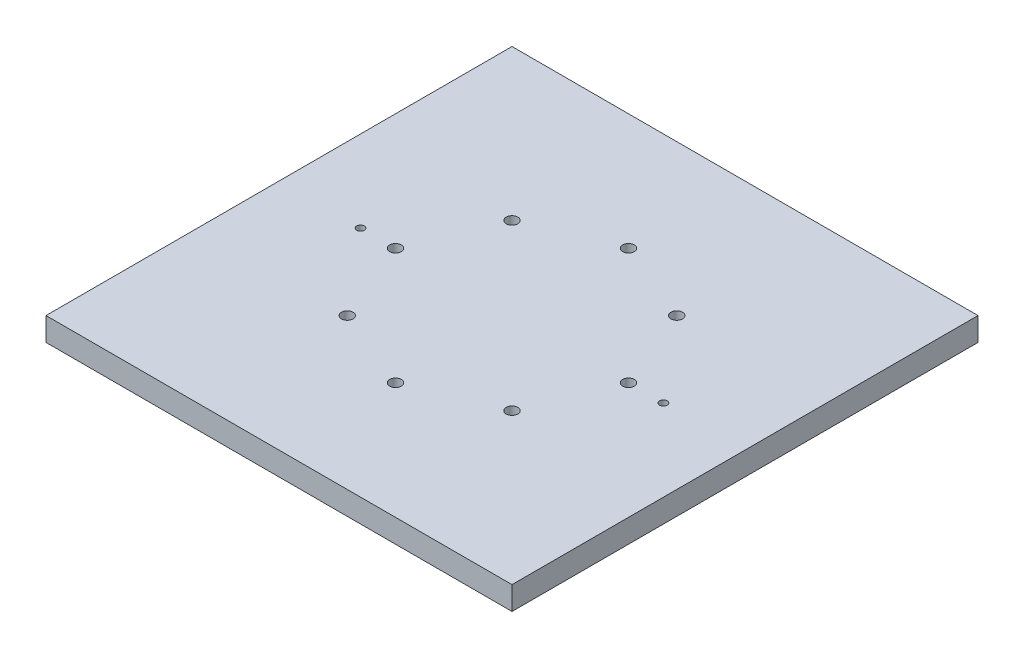
SolidWorks part; units mm, degrees
ref_plane "Front Plane" through (0, 0, 0) normal (0, 0, 1) x (1, 0, 0)
ref_plane "Top Plane" through (0, 0, 0) normal (0, 1, 0) x (1, 0, 0)
ref_plane "Right Plane" through (0, 0, 0) normal (1, 0, 0) x (0, 0, -1)
sketch "Sketch1" plane through (0, 0, 0) normal (0, 1, 0) x (1, 0, 0)
  line L1 (-127, -127) -> (127, -127)
  line L2 (-127, -127) -> (-127, 127)
  line L3 (-127, 127) -> (127, 127)
  line L4 (127, -127) -> (127, 127)
  line L5 (-127, -127) -> (127, 127) construction
  line L6 (-127, 127) -> (127, -127) construction
  point P0 (0, 0)
  dimension "D1" = 254
  dimension "D2" = 254
extrude "Boss-Extrude1" add sketch "Sketch1" along normal blind 12.7
sketch "Sketch6" plane through (0, 12.7, 0) normal (0, 1, 0) x (1, 0, 0)
  line L0 (0, 201.7673) -> (0, -205.4428) construction
  line L1 (-235.5165, 0) -> (339.2624, 0) construction
  circle A0 centre (0, 63.5) radius 3.175
  circle A1 centre (44.9013, 44.9013) radius 3.175
  circle A2 centre (63.5, 0) radius 3.175
  circle A3 centre (44.9013, -44.9013) radius 3.175
  circle A4 centre (0, -63.5) radius 3.175
  circle A5 centre (-44.9013, -44.9013) radius 3.175
  circle A6 centre (-63.5, 0) radius 3.175
  circle A7 centre (-44.9013, 44.9013) radius 3.175
  point P23 (0, 0)
  dimension "D1" = 6.35
  dimension "D2" = 63.5
  dimension "D3" = 8
extrude "Cut-Extrude2" cut sketch "Sketch6" against normal through all both and the other way through all
sketch "Sketch7" plane through (0, 12.7, 0) normal (0, 1, 0) x (1, 0, 0)
  line L0 (179.6043, 0) -> (-179.6043, 0) construction
  circle A0 centre (-82.55, 0) radius 2.0828
  circle A1 centre (82.55, 0) radius 2.0828
  point P4 (0, 0)
  dimension "D1" = 4.1656
  dimension "D2" = 82.55
  dimension "D3" = 82.55
extrude "Cut-Extrude3" cut sketch "Sketch7" against normal through all both and the other way through all
